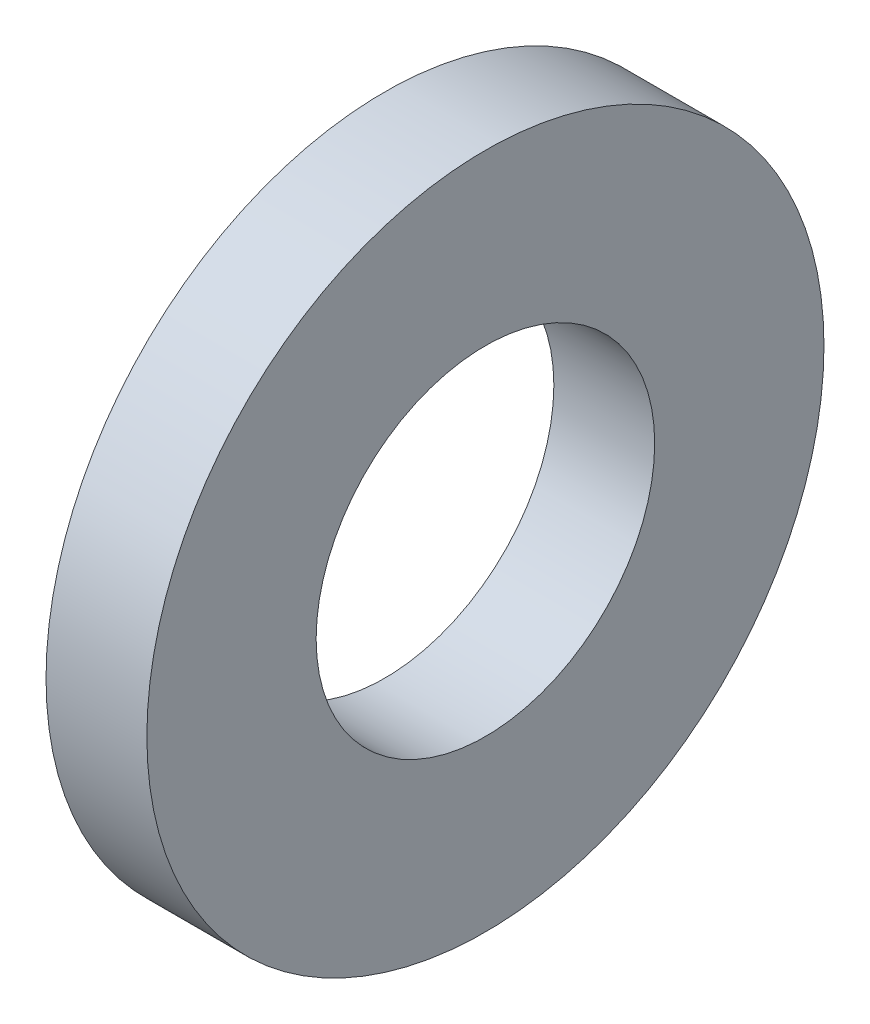
SolidWorks part; units mm, degrees
ref_plane "Front Plane" through (0, 0, 0) normal (0, 0, 1) x (1, 0, 0)
ref_plane "Top Plane" through (0, 0, 0) normal (0, 1, 0) x (1, 0, 0)
ref_plane "Right Plane" through (0, 0, 0) normal (1, 0, 0) x (0, 0, -1)
sketch "Sketch1" plane through (0, 0, 0) normal (1, 0, 0) x (0, 0, -1)
  circle A0 centre (0, 0) radius 2.3876
  circle A1 centre (0, 0) radius 1.1938
  dimension "OD" = 4.7752
  dimension "ID" = 2.3876
extrude "Boss-Extrude1" add sketch "Sketch1" along normal blind 0.7112
